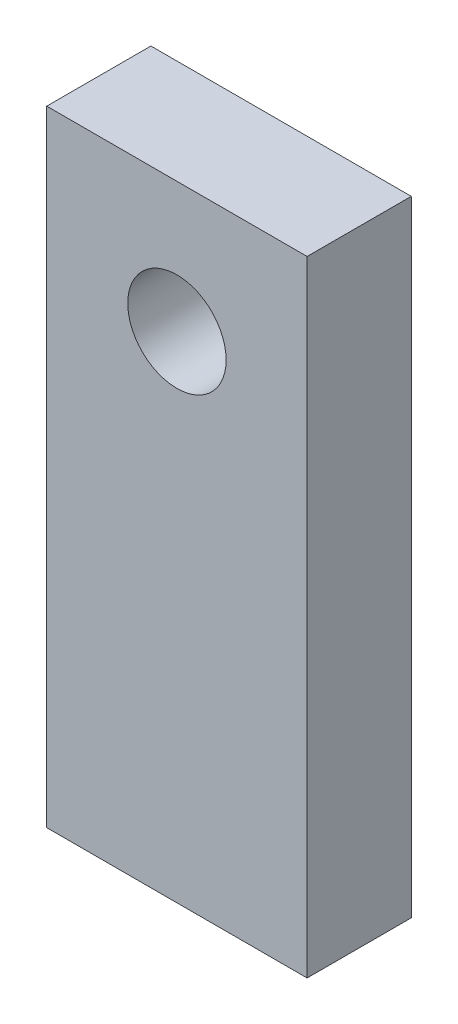
SolidWorks part; units mm, degrees
ref_plane "Front Plane" through (0, 0, 0) normal (0, 0, 1) x (1, 0, 0)
ref_plane "Top Plane" through (0, 0, 0) normal (0, 1, 0) x (1, 0, 0)
ref_plane "Right Plane" through (0, 0, 0) normal (1, 0, 0) x (0, 0, -1)
sketch "Sketch1" plane through (0, 0, 0) normal (0, 0, 1) x (1, 0, 0)
  line L0 (0, 0) -> (0, 15.24)
  line L1 (0, 15.24) -> (6.35, 15.24)
  line L2 (6.35, 15.24) -> (6.35, 0)
  line L3 (6.35, 0) -> (0, 0)
  dimension "D1" = 6.35
  dimension "D2" = 15.24
extrude "Boss-Extrude1" add sketch "Sketch1" along normal blind 2.54
sketch "Sketch2" plane through (0, 0, 2.54) normal (0, 0, 1) x (1, 0, 0)
  line L0 (3.175, 15.24) -> (3.175, 12.065) construction
  line L1 (6.35, 15.24) -> (0, 15.24) construction
  dimension "D1" = 3.175
hole_wizard "M2 Clearance Hole1" positions "3DSketch1" profile "Sketch3" hole size "M2" standard "Ansi Metric"
sketch3d "3DSketch1"
  point P0 (3.175, 12.065, 2.54)
sketch "Sketch3" plane through (3.175, 12.065, 2.54) normal (1, 0, 0) x (0, -1, 0)
  line L0 (0, 0) -> (0, 10.721)
  line L1 (0, 10.721) -> (1.2, 10)
  line L2 (1.2, 10) -> (1.2, 0)
  line L5 (1.2, 0) -> (0, 0)
  line L10 (0, 10.721) -> (-1.2, 10) construction
  line L11 (0, -6.35) -> (0, 107.95) construction
  dimension "Hole Dia." = 2.4
  dimension "Hole Depth" = 10
  dimension "Drill Angle" = 118
